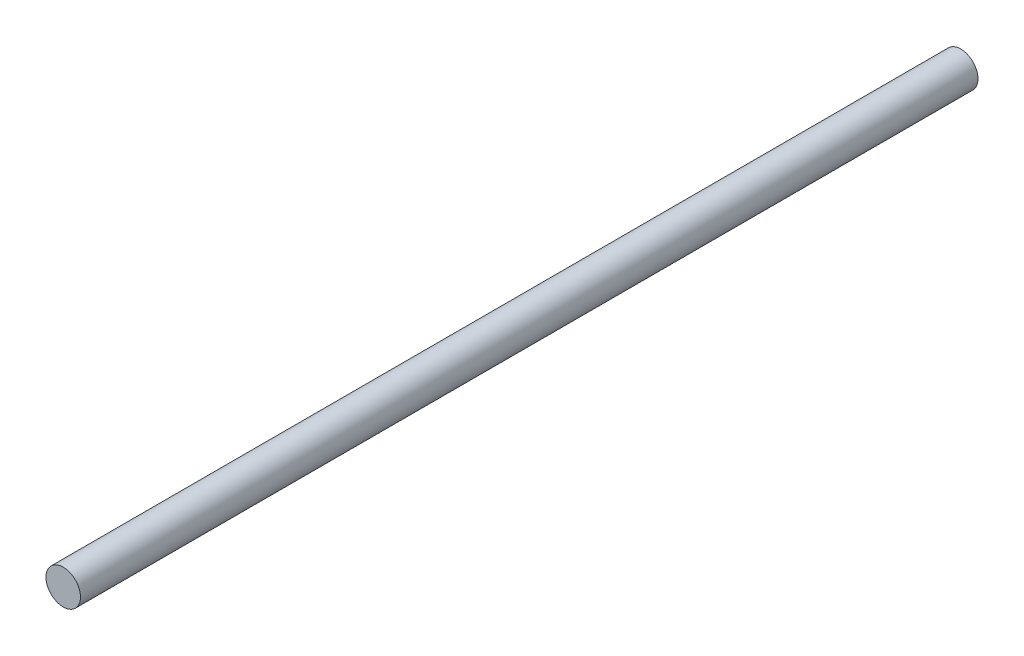
SolidWorks part; units mm, degrees
material "Magnesium Alloy"
ref_plane "Front Plane" through (0, 0, 0) normal (0, 0, 1) x (1, 0, 0)
ref_plane "Top Plane" through (0, 0, 0) normal (0, 1, 0) x (1, 0, 0)
ref_plane "Right Plane" through (0, 0, 0) normal (1, 0, 0) x (0, 0, -1)
sketch "Sketch1" plane through (0, 0, 0) normal (0, 0, 1) x (1, 0, 0)
  circle A0 centre (0, 0) radius 4.7625
  dimension "D1" = 0
  dimension "D2" = 9.525
extrude "Boss-Extrude1" add sketch "Sketch1" along normal blind 247.65
